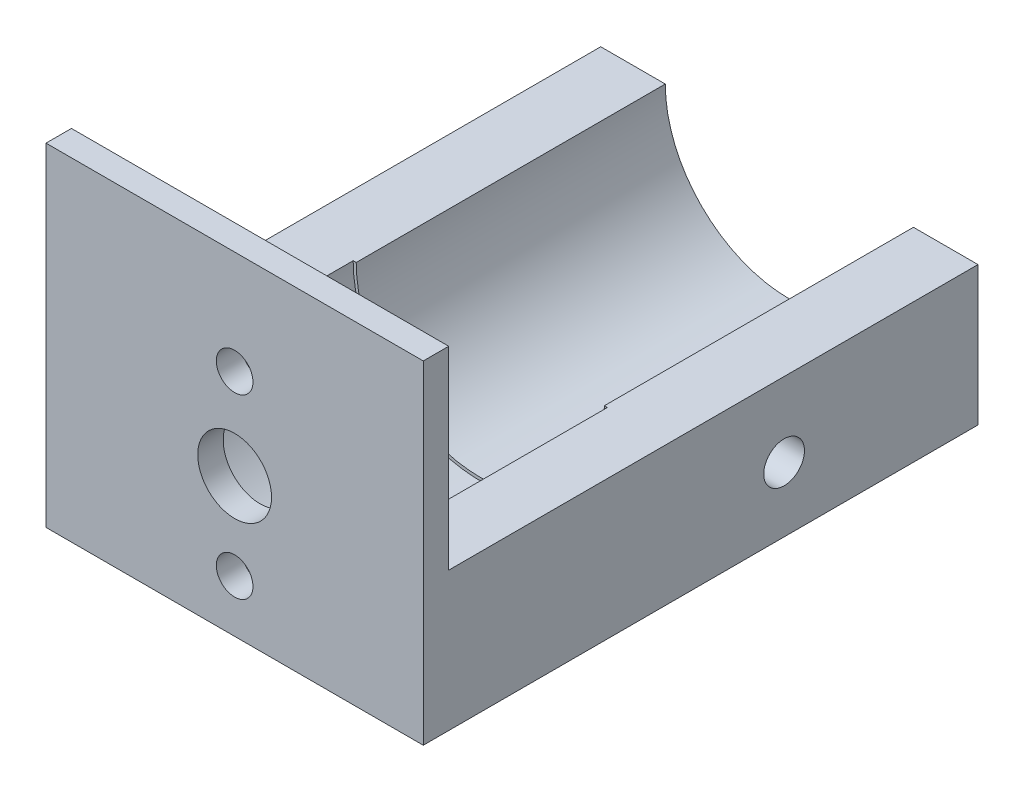
SolidWorks part; units mm, degrees
ref_plane "Front Plane" through (0, 0, 0) normal (0, 0, 1) x (1, 0, 0)
ref_plane "Top Plane" through (0, 0, 0) normal (0, 1, 0) x (1, 0, 0)
ref_plane "Right Plane" through (0, 0, 0) normal (1, 0, 0) x (0, 0, -1)
sketch "Sketch1" plane through (0, 0, 0) normal (0, 0, 1) x (1, 0, 0)
  line L7 (23.7638, 19.05) -> (23.7638, 5.4)
  line L10 (-13.3009, 19.05) -> (-13.3009, 5.4)
  line L12 (-13.3009, 19.05) -> (-6.9589, 19.05)
  line L13 (23.7638, 19.05) -> (17.4218, 19.05)
  line L14 (-13.3009, 5.4) -> (23.7638, 5.4)
  arc A1 (17.4218, 19.05) -> (-6.9589, 19.05) centre (5.2314, 19.05) cw
  dimension "D2" = 6.342
  dimension "D1" = 13.65
  dimension "D3" = 6.342
  dimension "D5" = 37.0648
extrude "Boss-Extrude1" add sketch "Sketch1" along normal blind 30.365
sketch "Sketch3" plane through (0, 0, 30.365) normal (0, 0, 1) x (1, 0, 0)
  line L1 (-13.3009, 19.05) -> (-13.3009, 5.4)
  line L3 (-13.3009, 5.4) -> (23.7638, 5.4)
  line L14 (-13.3009, 19.05) -> (-7.2589, 19.05)
  line L15 (-6.9589, 19.05) -> (-13.3009, 19.05) construction
  line L16 (17.7218, 19.05) -> (23.7638, 19.05)
  line L17 (23.7638, 19.05) -> (23.7638, 5.4)
  arc A0 (17.7218, 19.05) -> (-7.2589, 19.05) centre (5.2314, 19.05) cw
  dimension "D1" = 6.042
  dimension "D2" = 13.65
  dimension "D4" = 37.0648
extrude "Boss-Extrude2" add sketch "Sketch3" along normal blind 21.635
sketch "Sketch4" plane through (0, 0, 52) normal (0, 0, 1) x (1, 0, 0)
  line L1 (-13.3009, 5.4) -> (23.7638, 5.4)
  line L2 (-13.3009, 5.4) -> (-13.3009, 38.1)
  line L3 (-13.3009, 38.1) -> (23.7638, 38.1)
  line L4 (23.7638, 5.4) -> (23.7638, 38.1)
  circle A0 centre (5.2314, 19.05) radius 3.625
  circle A1 centre (5.2314, 10.541) radius 1.8
  circle A2 centre (5.2314, 27.94) radius 1.8
  dimension "D4" = 18.5324
  dimension "D5" = 7.25
  dimension "D6" = 3.6
  dimension "D7" = 3.6
  dimension "D10" = 8.89
  dimension "D11" = 8.509
  dimension "D1" = 37.0648
  dimension "D2" = 32.7
  dimension "D3" = 13.65
  dimension "D8" = 0
  dimension "D9" = 0
extrude "Boss-Extrude3" add sketch "Sketch4" along normal blind 2.5
sketch "Sketch5" plane through (0, 5.4, 0) normal (0, -1, 0) x (1, 0, 0)
  line L0 (-13.3009, 54.5) -> (-13.3009, 0) construction
  line L1 (-13.3009, 54.5) -> (23.7638, 54.5) construction
  line L2 (23.7638, 54.5) -> (23.7638, 0) construction
  line L3 (-13.3009, 0) -> (23.7638, 0) construction
  circle A0 centre (-8.2209, 48.15) radius 2
  circle A1 centre (18.6838, 48.15) radius 2
  circle A2 centre (-8.2209, 6.35) radius 2
  circle A3 centre (18.6838, 6.35) radius 2
  dimension "D1" = 4
  dimension "D2" = 4
  dimension "D3" = 4
  dimension "D4" = 4
  dimension "D6" = 6.35
  dimension "D7" = 5.08
  dimension "D8" = 6.35
  dimension "D9" = 5.08
  dimension "D10" = 6.35
  dimension "D11" = 5.08
  dimension "D12" = 6.35
  dimension "D5" = 5.08
extrude "Cut-Extrude1" cut sketch "Sketch5" against normal blind 7
sketch "Sketch6" plane through (-13.3009, 0, 0) normal (-1, 0, 0) x (0, 0, 1)
  line L0 (0, 19.05) -> (0, 5.4) construction
  line L1 (54.5, 5.4) -> (0, 5.4) construction
  circle A0 centre (19.05, 11.75) radius 2
  dimension "D1" = 4
  dimension "D2" = 19.05
  dimension "D3" = 6.35
extrude "Cut-Extrude2" cut sketch "Sketch6" against normal blind 7
sketch "Sketch7" plane through (23.7638, 0, 0) normal (1, 0, 0) x (0, 0, -1)
  line L0 (0, 5.4) -> (0, 19.05) construction
  line L1 (-54.5, 5.4) -> (0, 5.4) construction
  circle A0 centre (-19.05, 11.75) radius 2
  dimension "D1" = 4
  dimension "D2" = 19.05
  dimension "D3" = 6.35
extrude "Cut-Extrude3" cut sketch "Sketch7" against normal blind 7
